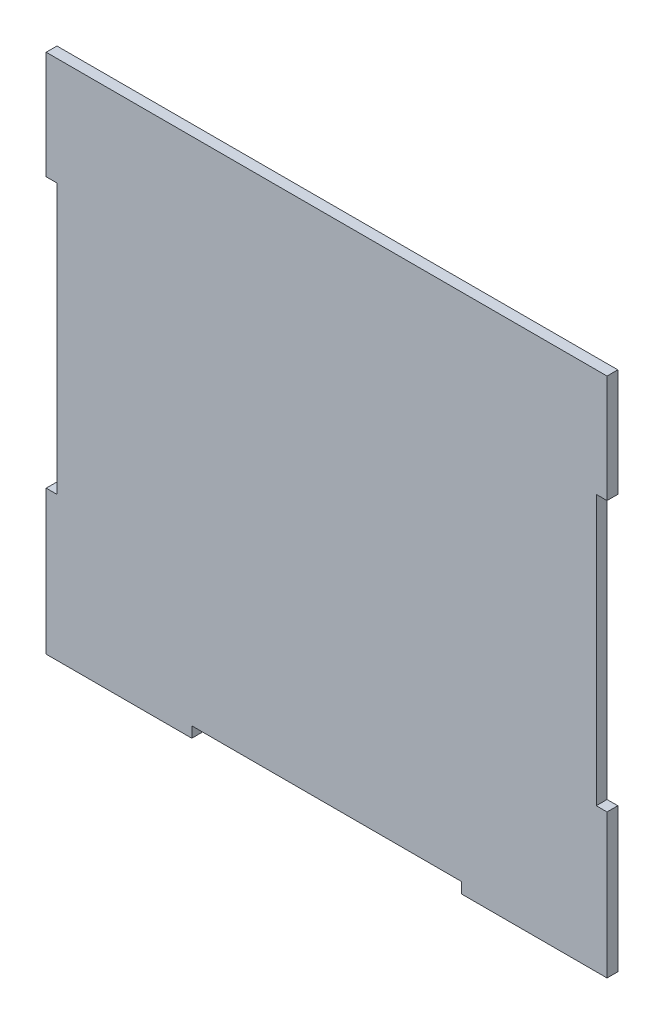
SolidWorks part; units mm, degrees
ref_plane "Alzado" through (0, 0, 0) normal (0, 0, 1) x (1, 0, 0)
ref_plane "Planta" through (0, 0, 0) normal (0, 1, 0) x (1, 0, 0)
ref_plane "Vista lateral" through (0, 0, 0) normal (1, 0, 0) x (0, 0, -1)
sketch "Croquis1" plane through (0, 0, 0) normal (0, 0, 1) x (1, 0, 0)
  line L0 (0, 115) -> (0, 145)
  line L1 (0, 0) -> (40.5, 0)
  line L2 (0, 0) -> (0, 40)
  line L3 (0, 145) -> (156, 145)
  line L4 (156, 0) -> (156, 40)
  line L6 (40.5, 0) -> (40.5, 3)
  line L7 (40.5, 3) -> (115.5, 3)
  line L8 (115.5, 0) -> (115.5, 3)
  line L9 (0, 115) -> (3, 115)
  line L11 (0, 40) -> (3, 40)
  line L12 (3, 115) -> (3, 40)
  line L13 (156, 115) -> (153, 115)
  line L15 (156, 40) -> (153, 40)
  line L16 (153, 115) -> (153, 40)
  line L17 (156, 115) -> (156, 145)
  line L18 (115.5, 0) -> (156, 0)
  dimension "D1" = 156
  dimension "D2" = 145
  dimension "D3" = 75
  dimension "D4" = 75
  dimension "D5" = 75
  dimension "D6" = 40.5
  dimension "D7" = 3
  dimension "D8" = 40
  dimension "D9" = 40
  dimension "D10" = 3
  dimension "D11" = 3
extrude "Saliente-Extruir1" add sketch "Croquis1" along normal blind 3
